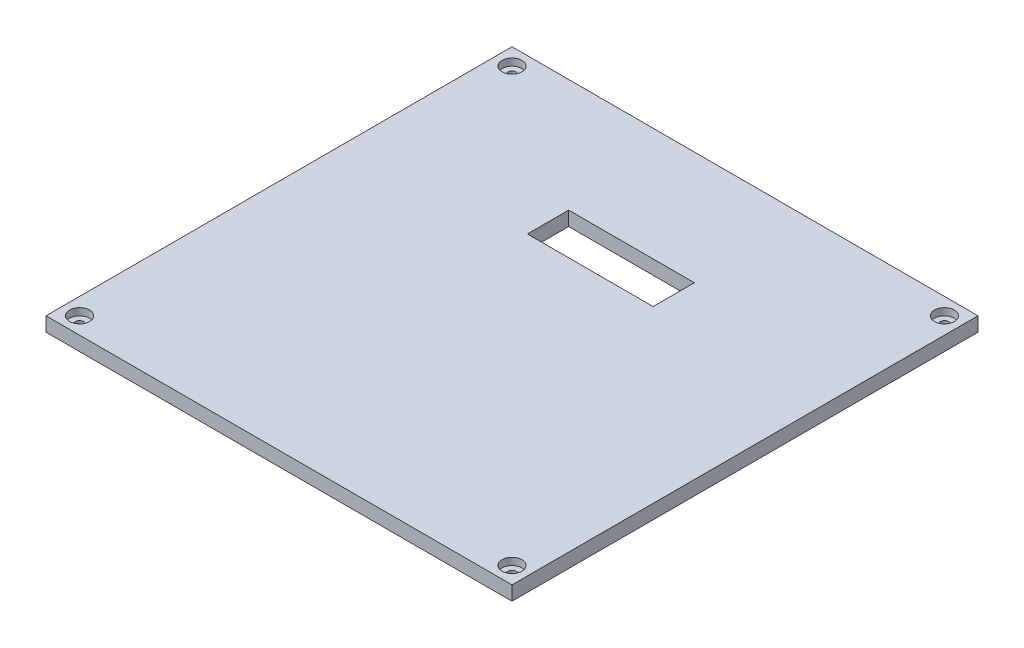
SolidWorks part; units mm, degrees
material "Custom Plastic"
ref_plane "Front Plane" through (0, 0, 0) normal (0, 0, 1) x (1, 0, 0)
ref_plane "Top Plane" through (0, 0, 0) normal (0, 1, 0) x (1, 0, 0)
ref_plane "Right Plane" through (0, 0, 0) normal (1, 0, 0) x (0, 0, -1)
sketch "Sketch1" plane through (0, 0, 0) normal (0, 1, 0) x (1, 0, 0)
  line L1 (0, 0) -> (416.08, 0)
  line L2 (0, 0) -> (0, 416.08)
  line L3 (0, 416.08) -> (416.08, 416.08)
  line L4 (416.08, 0) -> (416.08, 416.08)
  point P5 (0, 0)
extrude "Boss-Extrude1" add sketch "Sketch1" along normal blind 12.7 contours L2 L1 L4 L3
sketch "Sketch2" plane through (0, 12.7, 0) normal (0, 1, 0) x (1, 0, 0)
  line L8 (0, 0) -> (416.08, 0) construction
  line L9 (0, 0) -> (0, 416.08) construction
  circle A0 centre (14.986, 14.986) radius 3.683
  dimension "D5" = 7.366
  dimension "D1" = 14.986
  dimension "D2" = 14.986
extrude "Cut-Extrude1" cut sketch "Sketch2" against normal through all
sketch "Sketch3" plane through (0, 12.7, 0) normal (0, 1, 0) x (1, 0, 0)
  circle A0 centre (14.986, 14.986) radius 8.89
  dimension "D1" = 17.78
extrude "Cut-Extrude2" cut sketch "Sketch3" against normal mid plane 12.7
ref_plane "Plane1" through (208.04, 0, 0) normal (-1, 0, 0) x (0, 0, 1)
ref_plane "Plane2" through (0, 0, -208.04) normal (0, 0, -1) x (-1, 0, 0)
mirror "Mirror1" about plane through (0, 0, -208.04) normal (0, 0, -1) of "Cut-Extrude2", "Cut-Extrude1" second plane through (208.04, 0, 0) second plane normal (-1, 0, 0)
sketch "Sketch4" plane through (0, 0, 0) normal (0, -1, 0) x (1, 0, 0)
  line L1 (151.6366, -278.1873) -> (263.8806, -278.1873)
  line L2 (151.6366, -278.1873) -> (151.6366, -315.0308)
  line L3 (151.6366, -315.0308) -> (263.8806, -315.0308)
  line L4 (263.8806, -278.1873) -> (263.8806, -315.0308)
extrude "Cut-Extrude3" cut sketch "Sketch4" against normal up to next
